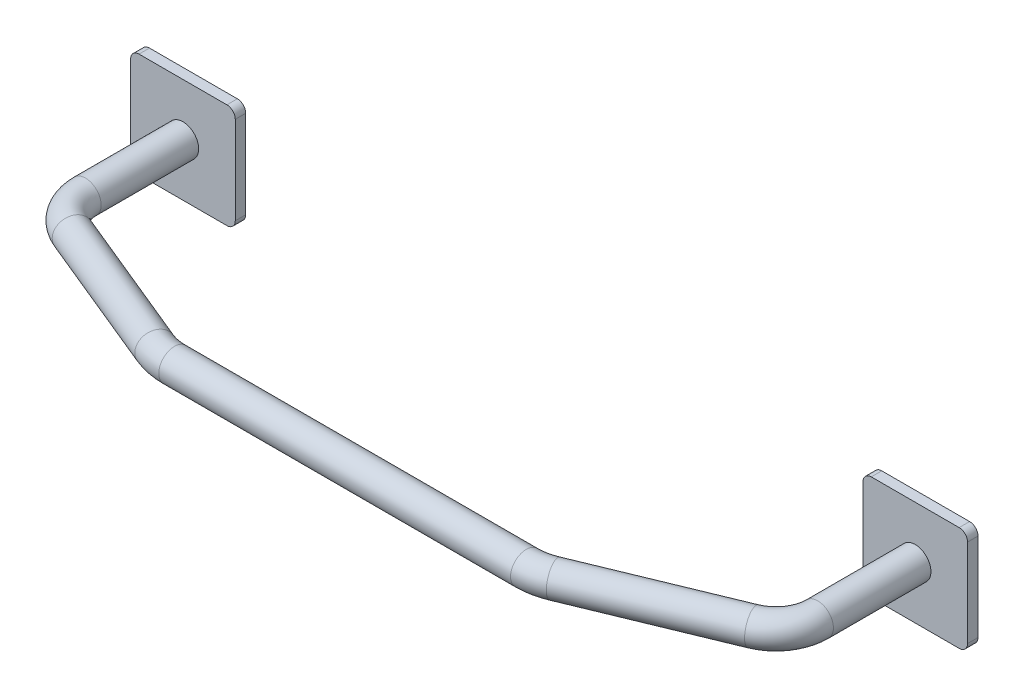
SolidWorks part; units mm, degrees
ref_plane "Front Plane" through (0, 0, 0) normal (0, 0, 1) x (1, 0, 0)
ref_plane "Top Plane" through (0, 0, 0) normal (0, 1, 0) x (1, 0, 0)
ref_plane "Right Plane" through (0, 0, 0) normal (1, 0, 0) x (0, 0, -1)
other "Configuration Table"
sketch "Sketch1" plane through (0, 0, 0) normal (0, 0, 1) x (1, 0, 0)
  line L1 (-200, 25) -> (-150, 25)
  line L2 (-200, 25) -> (-200, -25)
  line L3 (-200, -25) -> (-150, -25)
  line L4 (-150, 25) -> (-150, -25)
  line L5 (-175, -25) -> (-175, 25) construction
  line L6 (-200, 0) -> (-150, 0) construction
  point P0 (-175, 0)
  point P4 (0, 0)
  dimension "D1" = 50
  dimension "D2" = 175
extrude "Boss-Extrude1" add sketch "Sketch1" along normal blind 5
sketch "Sketch2" plane through (0, 0, 0) normal (0, 1, 0) x (1, 0, 0)
  line L0 (-175, -5) -> (-175, -51.6061)
  line L1 (-150, -5) -> (-200, -5) construction
  line L2 (-162.615, -70.0997) -> (-95.4877, -97.7403)
  line L3 (-84.0652, -100) -> (0, -100)
  line L4 (-150, 0) -> (-200, 0) construction
  arc A0 (-95.4877, -97.7403) -> (-84.0652, -100) centre (-84.0652, -70) ccw
  arc A1 (-175, -51.6061) -> (-162.615, -70.0997) centre (-155, -51.6061) ccw
  point P4 (0, 0)
  point P12 (-90, -100)
  point P15 (-175, -65)
  dimension "D4" = 20
  dimension "D5" = 30
  dimension "D1" = 90
  dimension "D2" = 65
  dimension "D3" = 100
sweep "Sweep1" add path "Sketch2" circular profile diameter 15 parameters "D3"=15
fillet "Fillet1" radius 4 4 edges at (-150, -25, 2.5) (-200, -25, 2.5) (-150, 25, 2.5) (-200, 25, 2.5)
mirror "Mirror1" about plane through (0, 0, 0) normal (1, 0, 0) of bodies 111
equation "\"GAUGE\"= SWITCH ( \"Thickness\" < 0.9 , 0 , \"Thickness\" < 1.1 , 20 , \"Thickness\" < 1.6 , 16 , \"Thickness\" < 2.1 , 14 , \"Thickness\" < 3.1 , 11 , \"Thickness\" < 4.8 , 7 , \"Thickness\" > 4.8 , 0 )"
